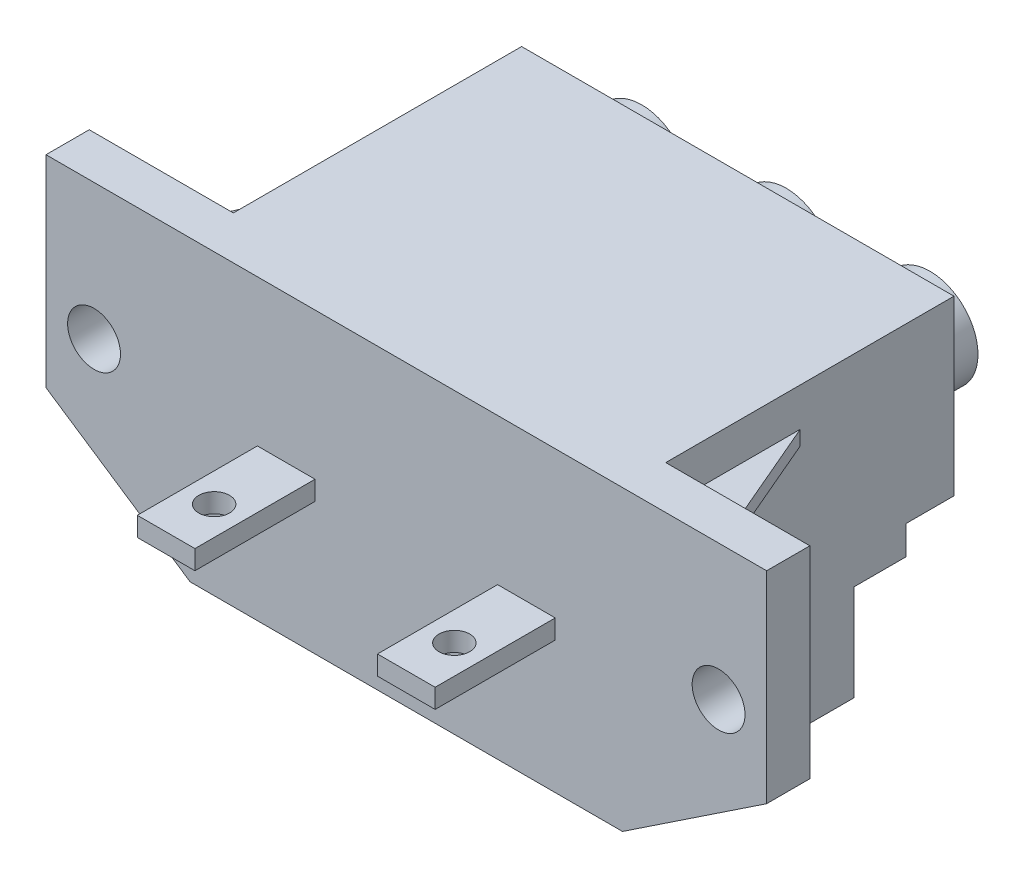
SolidWorks part; units mm, degrees
ref_plane "Спереди" through (0, 0, 0) normal (0, 0, 1) x (1, 0, 0)
ref_plane "Сверху" through (0, 0, 0) normal (0, 1, 0) x (1, 0, 0)
ref_plane "Справа" through (0, 0, 0) normal (1, 0, 0) x (0, 0, -1)
sketch "Эскиз1" plane through (0, 0, 0) normal (0, 0, 1) x (1, 0, 0)
  line L0 (-61.4223, 0) -> (72.2783, 0) construction
  line L1 (0, 51.5662) -> (0, -42.4242) construction
  line L2 (-22.5, -16.9) -> (-37.5, -6.9)
  line L3 (-22.5, -16.9) -> (22.5, -16.9)
  line L4 (-37.5, -6.9) -> (-37.5, 14.1)
  line L5 (-37.5, 14.1) -> (37.5, 14.1)
  line L6 (37.5, -6.9) -> (37.5, 14.1)
  line L7 (22.5, -16.9) -> (37.5, -6.9)
  circle A0 centre (-32.5, 0) radius 2.75
  circle A1 centre (32.5, 0) radius 2.75
  dimension "D6" = 5.5
  dimension "D7" = 65
  dimension "D1" = 31
  dimension "D2" = 75
  dimension "D3" = 14.1
  dimension "D4" = 15
  dimension "D5" = 10
extrude "Вытянуть1" add sketch "Эскиз1" along normal blind 4.5
sketch "Эскиз2" plane through (0, 0, 0) normal (1, 0, 0) x (0, 0, -1)
  line L0 (-4.5, 14.1) -> (0, 14.1) construction
  line L1 (0, -16.9) -> (19.6045, -16.9)
  line L2 (0, -16.9) -> (0, 14.1)
  line L3 (0, 14.1) -> (30, 14.1)
  line L4 (30, -3.9) -> (30, 14.1)
  line L5 (-4.5, -16.9) -> (0, -16.9) construction
  line L8 (19.6045, -16.9) -> (19.6045, -6.9)
  line L9 (19.6045, -6.9) -> (25, -6.9)
  line L10 (25, -6.9) -> (25, -3.9)
  line L11 (25, -3.9) -> (30, -3.9)
  dimension "D1" = 30
  dimension "D2" = 10
  dimension "D3" = 3
  dimension "D4" = 5
extrude "Вытянуть2" add sketch "Эскиз2" along normal blind 22.5 and the other way blind 22.5
sketch "Эскиз3" plane through (0, 0, -30) normal (0, 0, -1) x (-1, 0, 0)
  line L0 (0, 19.2629) -> (0, -20.9552) construction
  line L1 (-29.3115, 5.1) -> (29.2263, 5.1) construction
  line L2 (-22.5, -3.9) -> (22.5, -3.9) construction
  line L3 (-22.5, 14.1) -> (22.5, 14.1) construction
  circle A0 centre (-0.0426, 5.1) radius 3.5
  circle A1 centre (-15, 5.1) radius 5
  circle A2 centre (15, 5.1) radius 5
  circle A3 centre (-15, 5.1) radius 3.5
  circle A4 centre (-0.0426, 5.1) radius 5
  circle A5 centre (15, 5.1) radius 3.5
  dimension "D1" = 30
  dimension "D2" = 10
  dimension "D3" = 7
extrude "Вытянуть3" add sketch "Эскиз3" along normal blind 5
sketch "Эскиз4" plane through (0, -16.9, 0) normal (0, -1, 0) x (1, 0, 0)
  line L0 (0, 11.2633) -> (0, -37.6461) construction
  line L1 (22.5, 0) -> (22.5, -19.6045) construction
  line L2 (-31.2713, -7.5523) -> (29.0559, -7.5523) construction
  line L3 (-22.5, 4.5) -> (22.5, 4.5) construction
  line L4 (22.5, -19.6045) -> (-22.5, -19.6045) construction
  line L6 (5, -0.0523) -> (-5, -0.0523)
  line L7 (5, -0.0523) -> (5, -15.0523)
  line L8 (5, -15.0523) -> (-5, -15.0523)
  line L9 (-5, -0.0523) -> (-5, -15.0523)
  line L11 (7.5, -15.0523) -> (7.5, -0.0523)
  line L12 (17.5, -15.0523) -> (17.5, -0.0523)
  line L13 (17.5, -0.0523) -> (7.5, -0.0523)
  line L14 (17.5, -15.0523) -> (7.5, -15.0523)
  line L15 (-17.5, -15.0523) -> (-17.5, -0.0523)
  line L16 (-7.5, -0.0523) -> (-17.5, -0.0523)
  line L17 (-7.5, -15.0523) -> (-7.5, -0.0523)
  line L18 (-7.5, -15.0523) -> (-17.5, -15.0523)
  dimension "D1" = 10
  dimension "D2" = 15
  dimension "D3" = 7.5
  dimension "D4" = 7.5
  dimension "D5" = 22.5
  dimension "D6" = 10
  dimension "D7" = 2.5
  dimension "D8" = 15
extrude "Вырез-Вытянуть1" cut sketch "Эскиз4" against normal blind 5
sketch "Эскиз5" plane through (0, 0, 4.5) normal (0, 0, 1) x (1, 0, 0)
  line L0 (0, 19.3482) -> (0, -23.6819) construction
  line L1 (-39.6217, 0) -> (39.0252, 0) construction
  line L2 (-37.6021, 9.2084) -> (41.0448, 9.2084) construction
  line L3 (-11.6361, 2.9584) -> (10.6352, 2.9584) construction
  line L5 (-18.7535, -2.15) -> (-6.8616, -2.15) construction
  line L6 (-15.5, -3.15) -> (-9.5, -3.15)
  line L7 (-15.5, -3.15) -> (-15.5, -1.15)
  line L8 (-15.5, -1.15) -> (-9.5, -1.15)
  line L9 (-9.5, -3.15) -> (-9.5, -1.15)
  line L11 (9.5, -3.15) -> (9.5, -1.15)
  line L12 (15.5, -1.15) -> (9.5, -1.15)
  line L13 (15.5, -3.15) -> (15.5, -1.15)
  line L14 (15.5, -3.15) -> (9.5, -3.15)
  dimension "D1" = 2
  dimension "D5" = 9.5
  dimension "D6" = 6
extrude "Вытянуть4" add sketch "Эскиз5" along normal blind 12.5
sketch "Эскиз6" plane through (0, 0, 0) normal (0, 0, -1) x (-1, 0, 0)
  line L0 (-22.5, 14.1) -> (-22.5, -16.9) construction
  line L1 (-28.5, -8.9) -> (-22.5, -8.9)
  line L2 (-28.5, -8.9) -> (-28.5, -7.4)
  line L3 (-28.5, -7.4) -> (-22.5, -7.4)
  line L4 (-22.5, -8.9) -> (-22.5, -7.4)
  line L5 (-22.5, -16.9) -> (22.5, -16.9) construction
  line L6 (-21, 0.6) -> (22.5, 0.6) construction
  line L7 (22.5, 14.1) -> (22.5, -16.9) construction
  line L8 (0, 18.0386) -> (0, -18.9906) construction
  line L9 (-37.5, -6.9) -> (-37.5, 14.1) construction
  line L10 (37.5, 14.1) -> (37.5, -6.9) construction
  line L11 (-22.5, 10.1) -> (-22.5, 8.6)
  line L12 (-28.5, 8.6) -> (-22.5, 8.6)
  line L13 (-28.5, 10.1) -> (-28.5, 8.6)
  line L14 (-28.5, 10.1) -> (-22.5, 10.1)
  line L15 (28.5, 10.1) -> (22.5, 10.1)
  line L16 (28.5, 10.1) -> (28.5, 8.6)
  line L17 (28.5, 8.6) -> (22.5, 8.6)
  line L18 (22.5, 10.1) -> (22.5, 8.6)
  line L19 (22.5, -8.9) -> (22.5, -7.4)
  line L20 (28.5, -7.4) -> (22.5, -7.4)
  line L21 (28.5, -8.9) -> (28.5, -7.4)
  line L22 (28.5, -8.9) -> (22.5, -8.9)
  dimension "D1" = 8
  dimension "D2" = 1.5
  dimension "D3" = 6
  dimension "D4" = 8
extrude "Вытянуть5" add sketch "Эскиз6" along normal blind 14
sketch "Эскиз7" plane through (0, -8.9, 0) normal (0, -1, 0) x (1, 0, 0)
  line L0 (-22.5, -14) -> (-28.5, -14) construction
  line L1 (-22.5, -14) -> (-28.5, -14)
  line L2 (-28.5, -14) -> (-28.5, 0) construction
  line L3 (0, 8.9261) -> (0, -18.8635) construction
  line L4 (-22.5, 0) -> (-22.5, -19.6045) construction
  line L5 (22.5, 0) -> (22.5, -19.6045) construction
  line L6 (-28.5, -14) -> (-28.5, 0)
  line L7 (-22.5, -14) -> (-28.5, 0)
  line L8 (22.5, -14) -> (28.5, 0)
  line L11 (28.5, -14) -> (28.5, 0)
  line L12 (22.5, -14) -> (28.5, -14)
extrude "Вырез-Вытянуть2" cut sketch "Эскиз7" against normal blind 20
sketch "Эскиз8" plane through (0, -3.15, 0) normal (0, -1, 0) x (1, 0, 0)
  line L0 (-12.5, 12) -> (-12.5, 19.6119) construction
  line L1 (-15.5, 17) -> (-15.5, 4.5) construction
  line L2 (-9.5, 17) -> (-9.5, 4.5) construction
  line L3 (-15.5, 17) -> (-9.5, 17) construction
  line L4 (0, 0) -> (0, 11.0628) construction
  circle A0 centre (-12.5, 12) radius 1.6
  circle A1 centre (12.5, 12) radius 1.6
  dimension "D1" = 3.2
  dimension "D2" = 5
extrude "Вырез-Вытянуть3" cut sketch "Эскиз8" against normal blind 10
